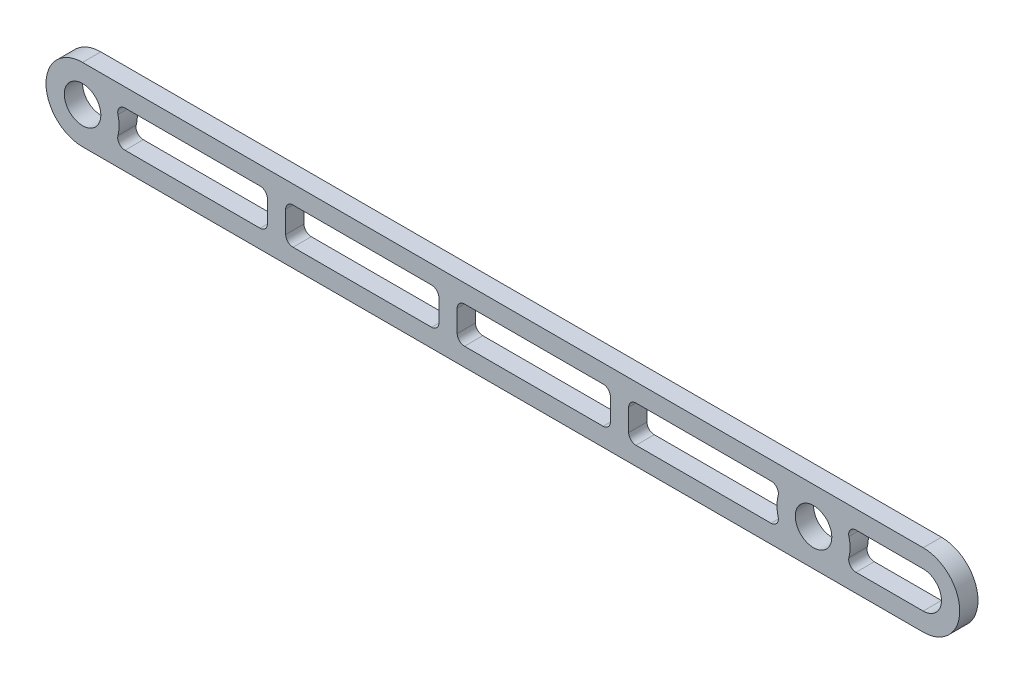
SolidWorks part; units mm, degrees
ref_plane "Front" through (0, 0, 0) normal (0, 0, 1) x (1, 0, 0)
ref_plane "Top" through (0, 0, 0) normal (0, 1, 0) x (1, 0, 0)
ref_plane "Right" through (0, 0, 0) normal (1, 0, 0) x (0, 0, -1)
sketch "草图1" plane through (0, 0, 0) normal (0, 0, 1) x (1, 0, 0)
  line L0 (0, 0) -> (230, 0) construction
  line L1 (0, 10) -> (230, 10)
  line L2 (0, -10) -> (230, -10)
  line L3 (8.6603, 5) -> (50.5801, 5)
  line L4 (8.6603, -5) -> (50.5801, -5)
  line L5 (208.6603, 5) -> (230, 5)
  line L6 (208.6603, -5) -> (230, -5)
  line L7 (102.5, -5) -> (144.4199, -5)
  line L8 (102.5, 5) -> (102.5, -5)
  line L9 (97.5, 5) -> (97.5, -5)
  line L10 (102.5, 5) -> (144.4199, 5)
  line L11 (55.5801, -5) -> (97.5, -5)
  line L12 (55.5801, -5) -> (55.5801, 5)
  line L13 (50.5801, 5) -> (50.5801, -5)
  line L14 (55.5801, 5) -> (97.5, 5)
  line L15 (149.4199, -5) -> (191.3397, -5)
  line L16 (149.4199, -5) -> (149.4199, 5)
  line L17 (144.4199, -5) -> (144.4199, 5)
  line L18 (149.4199, 5) -> (191.3397, 5)
  arc A0 (0, 10) -> (0, -10) centre (0, 0) ccw
  arc A1 (230, -10) -> (230, 10) centre (230, 0) ccw
  circle A2 centre (0, 0) radius 5
  circle A3 centre (200, 0) radius 5
  arc A4 (191.3397, 5) -> (191.3397, -5) centre (200, 0) ccw
  arc A5 (208.6603, -5) -> (208.6603, 5) centre (200, 0) ccw
  arc A6 (230, -5) -> (230, 5) centre (230, 0) ccw
  arc A7 (8.6603, -5) -> (8.6603, 5) centre (0, 0) ccw
  point P3 (115, 0)
  dimension "D1" = 10
  dimension "D3" = 10
  dimension "D4" = 10
  dimension "D6" = 5
  dimension "D2" = 230
  dimension "D5" = 200
  dimension "D7" = 5
extrude "凸台-拉伸1" add sketch "草图1" along normal blind 5
fillet "圆角1" radius 2 1 edges at (50.5801, 5, 2.5)
fillet "圆角2" radius 2 17 edges at (208.6603, 5, 2.5) (208.6603, -5, 2.5) (191.3397, -5, 2.5) (191.3397, 5, 2.5) (149.4199, -5, 2.5) (149.4199, 5, 2.5) (144.4199, 5, 2.5) (144.4199, -5, 2.5) (102.5, 5, 2.5) (102.5, -5, 2.5) (97.5, -5, 2.5) (97.5, 5, 2.5) (55.5801, 5, 2.5) (55.5801, -5, 2.5) (50.5801, -5, 2.5) (8.6603, -5, 2.5) (8.6603, 5, 2.5)
